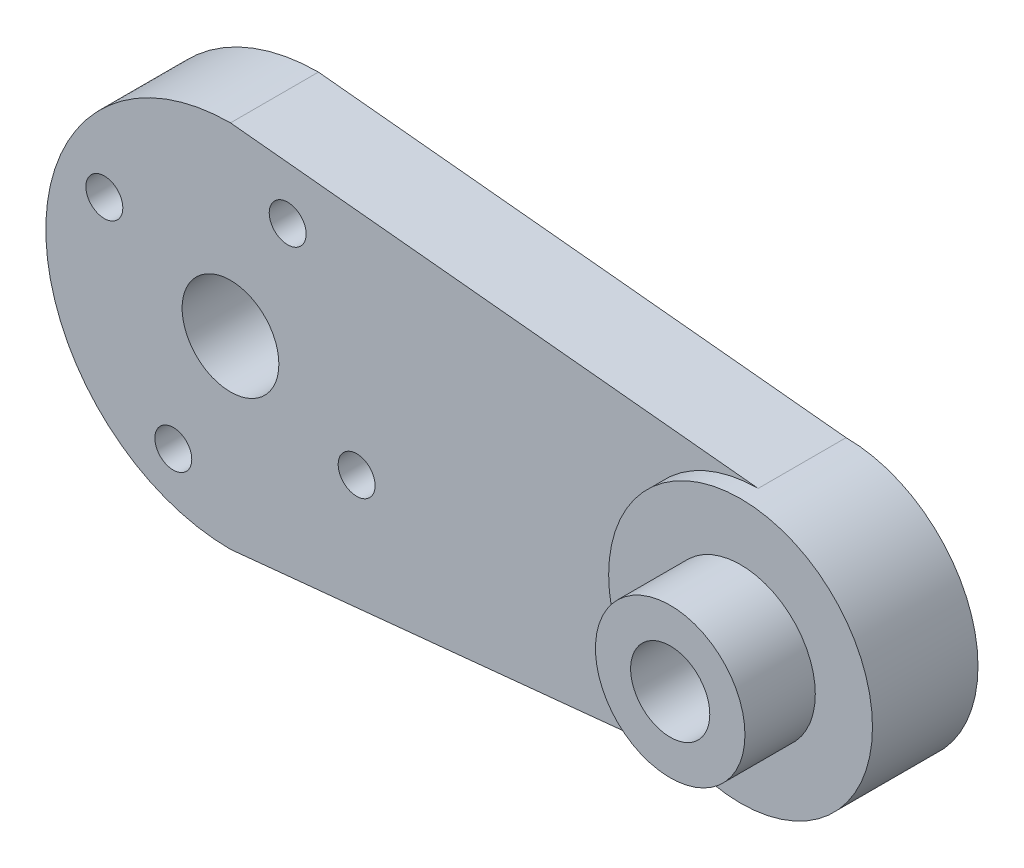
SolidWorks part; units mm, degrees
ref_plane "Front" through (0, 0, 0) normal (0, 0, 1) x (1, 0, 0)
ref_plane "Top" through (0, 0, 0) normal (0, 1, 0) x (1, 0, 0)
ref_plane "Right" through (0, 0, 0) normal (1, 0, 0) x (0, 0, -1)
sketch "스케치1" plane through (0, 0, 0) normal (0, 0, 1) x (1, 0, 0)
  line L0 (0, 0) -> (30, 0) construction
  line L1 (0, 10.5) -> (30, 7.5)
  line L2 (30, -7.5) -> (0, -10.5)
  line L3 (0, 10.5) -> (0, -10.5) construction
  line L4 (30, 7.5) -> (30, -7.5) construction
  arc A0 (0, 10.5) -> (0, -10.5) centre (0, 0) ccw
  circle A1 centre (0, 0) radius 2.75
  arc A2 (30, -7.5) -> (30, 7.5) centre (30, 0) ccw
  dimension "D1" = 5.5
  dimension "D2" = 21
  dimension "D3" = 15
  dimension "D4" = 30
extrude "보스-돌출1" add sketch "스케치1" along normal blind 5
sketch "스케치2" plane through (0, 0, 5) normal (0, 0, 1) x (1, 0, 0)
  circle A0 centre (30, 0) radius 4.25
  arc A1 (30, -7.5) -> (30, 7.5) centre (30, 0) ccw construction
  dimension "D1" = 8.5
extrude "보스-돌출2" add sketch "스케치2" along normal blind 5
sketch "스케치3" plane through (0, 0, 10) normal (0, 0, 1) x (1, 0, 0)
  circle A0 centre (30, 0) radius 2.25
  circle A1 centre (30, 0) radius 4.25 construction
  dimension "D1" = 4.5
extrude "컷-돌출1" cut sketch "스케치3" against normal blind 40
hole_wizard "M1.8 여유 구멍1" positions "스케치6" profile "스케치7" hole size "M1.8" standard "KS" end condition up to next
sketch "스케치6" plane through (0, 0, 0) normal (0, 0, -1) x (-1, 0, 0)
  point P3 (-7.1723, -3.2518)
  point P12 (3.2518, -7.1723)
  point P21 (7.1723, 3.2518)
  point P30 (-3.2518, 7.1723)
sketch "스케치7" plane through (7.1723, -3.2518, 0) normal (1, 0, 0) x (0, 1, 0)
  line L0 (0, 0) -> (0, 5)
  line L1 (0, 5) -> (1.05, 5)
  line L2 (1.05, 5) -> (1.05, 0)
  line L5 (1.05, 0) -> (0, 0)
  line L11 (0, -6.35) -> (0, 107.95) construction
  dimension "관통 구멍 지름" = 2.1
  dimension "관통 구멍 깊이" = 5
sketch "스케치8" plane through (0, 0, 5) normal (0, 0, 1) x (1, 0, 0)
  circle A0 centre (30, 0) radius 7.5
  circle A1 centre (30, 0) radius 2.25
extrude "보스-돌출3" add sketch "스케치8" along normal blind 1
